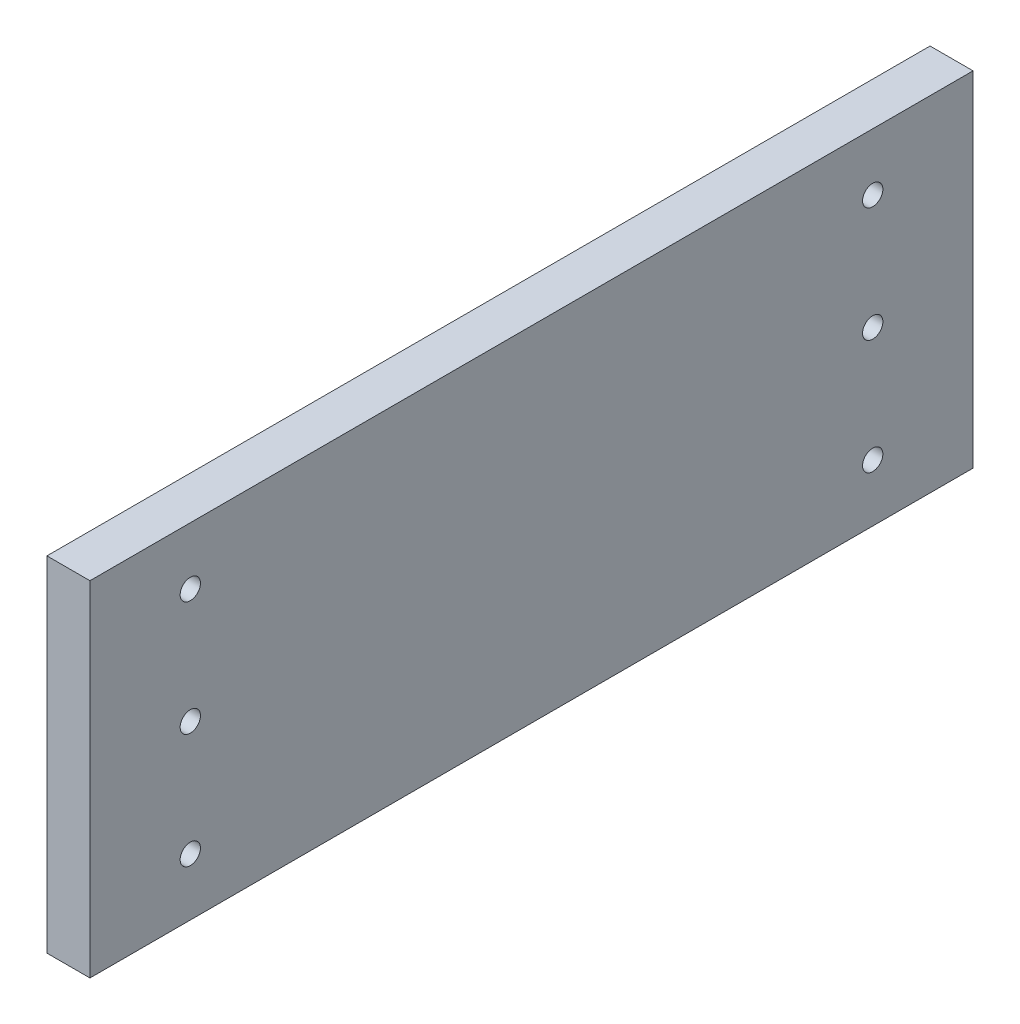
SolidWorks part; units mm, degrees
material "Plain Carbon Steel"
ref_plane "Front Plane" through (0, 0, 0) normal (0, 0, 1) x (1, 0, 0)
ref_plane "Top Plane" through (0, 0, 0) normal (0, 1, 0) x (1, 0, 0)
ref_plane "Right Plane" through (0, 0, 0) normal (1, 0, 0) x (0, 0, -1)
sketch "Sketch1" plane through (0, 0, 0) normal (0, 0, 1) x (1, 0, 0)
  line L1 (-4.7625, 38.1) -> (4.7625, 38.1)
  line L2 (-4.7625, 38.1) -> (-4.7625, -38.1)
  line L3 (-4.7625, -38.1) -> (4.7625, -38.1)
  line L4 (4.7625, 38.1) -> (4.7625, -38.1)
  line L5 (-4.7625, 38.1) -> (4.7625, -38.1) construction
  line L6 (-4.7625, -38.1) -> (4.7625, 38.1) construction
  point P0 (0, 0)
  dimension "D1" = 9.525
  dimension "D2" = 76.2
extrude "Boss-Extrude1" add sketch "Sketch1" along normal blind 195.58
hole_wizard "#8 Clearance Hole1" positions "Sketch3" profile "Sketch2" hole size "#8" standard "ANSI Inch" end condition through all
sketch "Sketch3" plane through (4.7625, 0, 0) normal (1, 0, 0) x (0, 0, -1)
  line L0 (-195.58, -38.1) -> (0, -38.1) construction
  line L1 (-195.58, -38.1) -> (-195.58, 38.1) construction
  line L2 (0, -38.1) -> (0, 38.1) construction
  point P0 (-173.355, 25.4)
  point P2 (-173.355, 0)
  point P4 (-173.355, -25.4)
  point P6 (-22.225, 25.4)
  point P8 (-22.225, 0)
  point P10 (-22.225, -25.4)
  point P17 (-195.58, 0)
  dimension "D1" = 25.4
  dimension "D2" = 25.4
  dimension "D3" = 12.7
  dimension "D4" = 22.225
  dimension "D5" = 22.225
sketch "Sketch2" plane through (4.7625, 25.4, 173.355) normal (0, 1, 0) x (0, 0, -1)
  line L0 (0, 0) -> (0, 9.525)
  line L1 (0, 9.525) -> (2.2479, 9.525)
  line L2 (2.2479, 9.525) -> (2.2479, 0)
  line L5 (2.2479, 0) -> (0, 0)
  line L11 (0, -6.35) -> (0, 107.95) construction
  dimension "Thru Hole Dia." = 4.4958
  dimension "Thru Hole Depth" = 9.525
